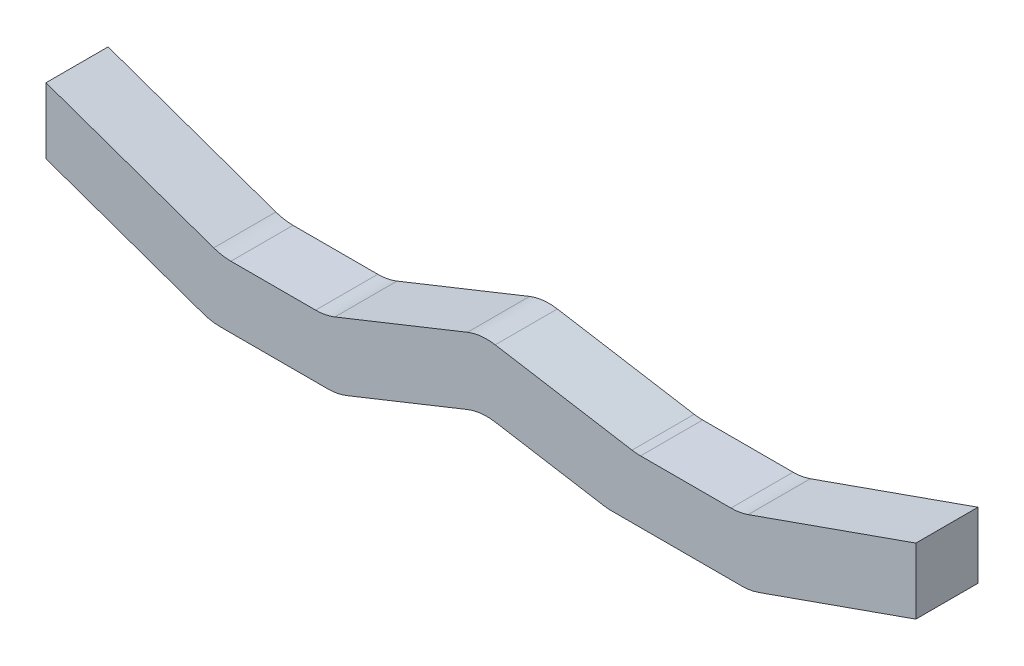
SolidWorks part; units mm, degrees
material "Pine"
ref_plane "Front Plane" through (0, 0, 0) normal (0, 0, 1) x (1, 0, 0)
ref_plane "Top Plane" through (0, 0, 0) normal (0, 1, 0) x (1, 0, 0)
ref_plane "Right Plane" through (0, 0, 0) normal (1, 0, 0) x (0, 0, -1)
sketch "Sketch1" plane through (0, 0, 0) normal (0, 0, 1) x (1, 0, 0)
  line L17 (0, -1000) -> (0, 49000) construction
  line L27 (0, 0) -> (47.625, -7.9375)
  line L28 (47.625, -7.9375) -> (79.375, -7.9375)
  line L30 (79.375, -7.9375) -> (133.35, 11.1125)
  line L37 (133.35, 11.1125) -> (133.35, -9.0892)
  line L38 (133.35, -9.0892) -> (82.6381, -26.9875)
  line L39 (82.6381, -26.9875) -> (38.8201, -26.9875)
  line L40 (38.8201, -26.9875) -> (0, -20.5175)
  line L42 (-43.9563, -38.1) -> (0, -20.5175)
  line L43 (-82.6381, -38.1) -> (-43.9563, -38.1)
  line L44 (-133.35, -20.2017) -> (-82.6381, -38.1)
  line L45 (-133.35, 0) -> (-133.35, -20.2017)
  line L46 (-79.375, -19.05) -> (-133.35, 0)
  line L47 (-47.625, -19.05) -> (-79.375, -19.05)
  line L48 (0, 0) -> (-47.625, -19.05)
  point P10 (-63.5, -19.05)
  point P14 (63.5, -7.9375)
  dimension "D2" = 266.7
  dimension "D3" = 7.9375
  dimension "D4" = 19.05
  dimension "D5" = 19.05
  dimension "D6" = 63.5
  dimension "D8" = 31.75
  dimension "D9" = 19.05
  dimension "D10" = 19.05
  dimension "D11" = 19.05
  dimension "D12" = 19.05
  dimension "D13" = 63.5
  dimension "D14" = 19.05
  dimension "D15" = 69.85
  dimension "D16" = 31.75
extrude "Boss-Extrude1" add sketch "Sketch1" along normal blind 19.05
hole_wizard "1/8 (0.125) Diameter Hole1" positions "Sketch4" profile "Sketch5" hole size "1/8" standard "ANSI Inch"
sketch "Sketch4" plane through (0, 0, 0) normal (0, 0, -1) x (-1, 0, 0)
  line L0 (0, 0) -> (0, -20.5175) construction
  line L1 (43.9563, -38.1) -> (0, -20.5175) construction
  line L3 (133.35, -10.1008) -> (103.4101, -20.6679) construction
  line L4 (133.35, 0) -> (133.35, -20.2017) construction
  line L6 (79.375, -19.05) -> (133.35, 0) construction
  line L9 (47.625, -19.05) -> (79.375, -19.05) construction
  line L10 (-133.35, 1.0117) -> (-103.4101, -9.5554) construction
  line L11 (-133.35, -9.0892) -> (-133.35, 11.1125) construction
  line L13 (-79.375, -7.9375) -> (-47.625, -7.9375) construction
  line L14 (-133.35, 11.1125) -> (-79.375, -7.9375) construction
  point P0 (-120.65, -3.4707)
  point P2 (0, -10.2587)
  point P4 (120.65, -14.5832)
  point P15 (0, -10.2587)
  dimension "D1" = 12.7
  dimension "D2" = 12.7
sketch "Sketch5" plane through (120.65, -3.4707, 0) normal (1, 0, 0) x (0, 1, 0)
  line L0 (0, 0) -> (0, 12.0791)
  line L1 (0, 12.0791) -> (1.5875, 11.1252)
  line L2 (1.5875, 11.1252) -> (1.5875, 0)
  line L5 (1.5875, 0) -> (0, 0)
  line L10 (0, 12.0791) -> (-1.5875, 11.1252) construction
  line L11 (0, -6.35) -> (0, 107.95) construction
  dimension "Hole Dia." = 3.175
  dimension "Hole Depth" = 11.1252
  dimension "Drill Angle" = 118
fillet "Fillet1" radius 15.875 10 edges at (79.375, -7.9375, 9.525) (47.625, -7.9375, 9.525) (82.6381, -26.9875, 9.525) (38.8201, -26.9875, 9.525) (0, -20.5175, 9.525) (-43.9563, -38.1, 9.525) (-82.6381, -38.1, 9.525) (-79.375, -19.05, 9.525) (-47.625, -19.05, 9.525) (0, 0, 9.525)
ref_plane "Plane1" through (-63.669, 0, 0) normal (-1, 0, 0) x (0, 0, 1)
hole_wizard "1/8 (0.125) Diameter Hole2" positions "Sketch6" profile "Sketch7" hole size "1/8" standard "ANSI Inch"
sketch "Sketch6" plane through (0, -26.9875, 0) normal (0, -1, 0) x (-1, 0, 0)
  point P0 (-73.116, -9.525)
  point P3 (-52.4785, -9.525)
sketch "Sketch7" plane through (73.116, -26.9875, 9.525) normal (1, 0, 0) x (0, 0, -1)
  line L0 (0, 0) -> (0, 12.0791)
  line L1 (0, 12.0791) -> (1.5875, 11.1252)
  line L2 (1.5875, 11.1252) -> (1.5875, 0)
  line L5 (1.5875, 0) -> (0, 0)
  line L10 (0, 12.0791) -> (-1.5875, 11.1252) construction
  line L11 (0, -6.35) -> (0, 107.95) construction
  dimension "Hole Dia." = 3.175
  dimension "Hole Depth" = 11.1252
  dimension "Drill Angle" = 118
hole_wizard "1/8 (0.125) Diameter Hole3" positions "Sketch8" profile "Sketch9" hole size "1/8" standard "ANSI Inch"
sketch "Sketch8" plane through (0, -38.1, 0) normal (0, -1, 0) x (-1, 0, 0)
  point P1 (53.3502, -9.525)
  point P4 (73.9877, -9.525)
sketch "Sketch9" plane through (-53.3502, -38.1, 9.525) normal (1, 0, 0) x (0, 0, -1)
  line L0 (0, 0) -> (0, 12.0791)
  line L1 (0, 12.0791) -> (1.5875, 11.1252)
  line L2 (1.5875, 11.1252) -> (1.5875, 0)
  line L5 (1.5875, 0) -> (0, 0)
  line L10 (0, 12.0791) -> (-1.5875, 11.1252) construction
  line L11 (0, -6.35) -> (0, 107.95) construction
  dimension "Hole Dia." = 3.175
  dimension "Hole Depth" = 11.1252
  dimension "Drill Angle" = 118
